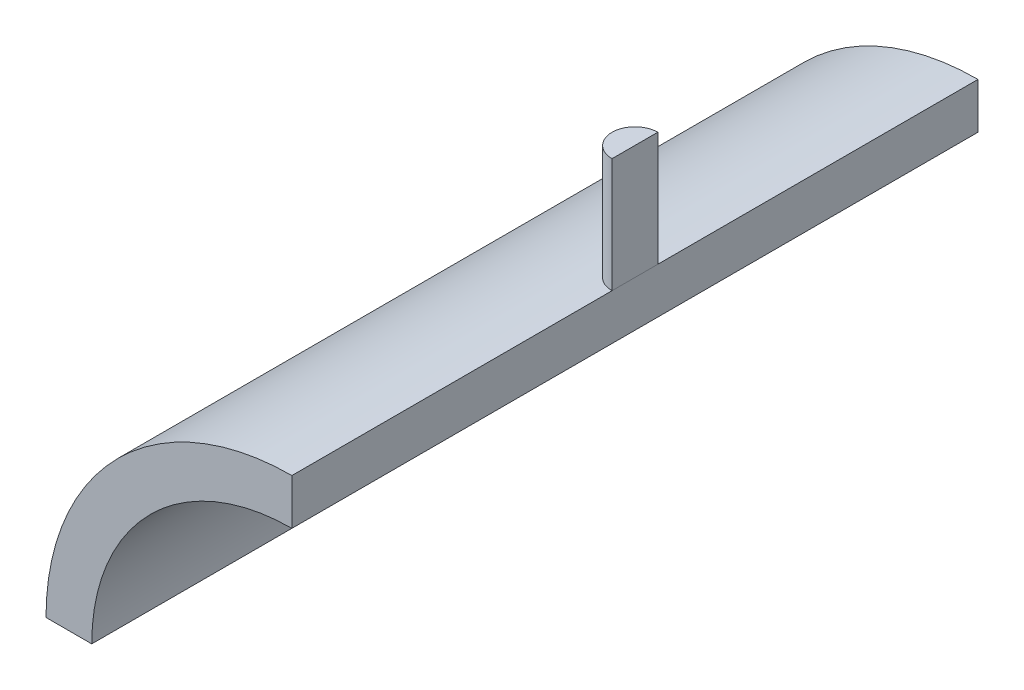
SolidWorks part; units mm, degrees
ref_plane "Front Plane" through (0, 0, 0) normal (0, 0, 1) x (1, 0, 0)
ref_plane "Top Plane" through (0, 0, 0) normal (0, 1, 0) x (1, 0, 0)
ref_plane "Right Plane" through (0, 0, 0) normal (1, 0, 0) x (0, 0, -1)
sketch "Sketch1" plane through (0, 0, 0) normal (0, 0, 1) x (1, 0, 0)
  line L2 (-27.305, 0) -> (-22.225, 0)
  line L3 (0, 22.225) -> (0, 27.305)
  arc A0 (-22.225, 0) -> (0, 22.225) centre (0, 0) cw
  arc A1 (-27.305, 0) -> (0, 27.305) centre (0, 0) cw
  dimension "D1" = 22.225
  dimension "D2" = 5.08
extrude "Boss-Extrude1" add sketch "Sketch1" along normal blind 76.2
ref_plane "Plane1" through (0, 27.305, 0) normal (0, 1, 0) x (1, 0, 0)
sketch "Sketch2" plane through (0, 27.305, 0) normal (0, 1, 0) x (1, 0, 0)
  line L0 (0, -76.2) -> (0, 0) construction
  line L1 (0, -35.56) -> (0, -40.64)
  arc A0 (0, -35.56) -> (0, -40.64) centre (0, -38.1) ccw
  dimension "D1" = 5.08
extrude "Boss-Extrude2" add sketch "Sketch2" along normal blind 12.7 and the other way up to next separate body
equation "\"D1@Sketch1\"=1.75/2"
